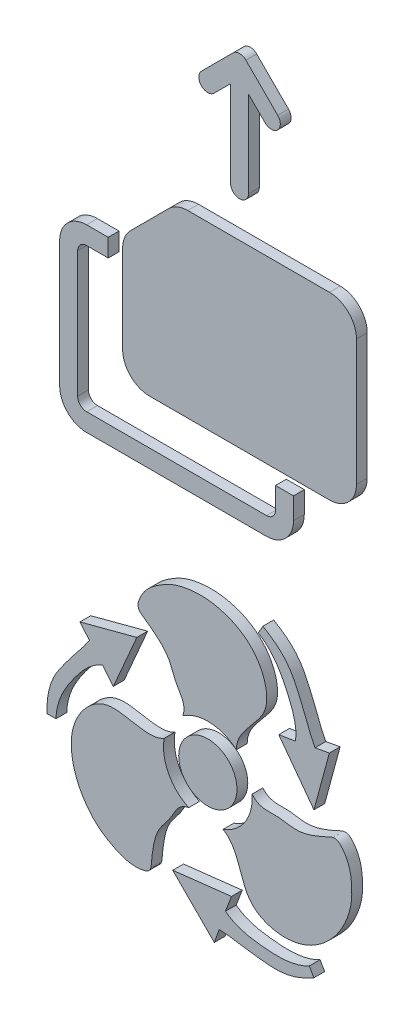
SolidWorks part; units mm, degrees
ref_plane "Plan de face" through (0, 0, 0) normal (0, 0, 1) x (1, 0, 0)
ref_plane "Plan de dessus" through (0, 0, 0) normal (0, 1, 0) x (1, 0, 0)
ref_plane "Plan de droite" through (0, 0, 0) normal (1, 0, 0) x (0, 0, -1)
sketch "Esquisse1" plane through (0, 0, 0) normal (0, 0, 1) x (1, 0, 0)
  line L0 (80.7187, -5.6862) -> (79.9221, -5.8311) construction
  line L1 (77.0254, -1.426) -> (76.7701, -1.8683) construction
  line L2 (78.8351, -6.0582) -> (77.9051, -6.2071) construction
  line L3 (77.9051, -6.2071) -> (79.8625, -8.8495) construction
  line L4 (79.8625, -8.8495) -> (80.7187, -5.6862) construction
  line L5 (66.8516, -6.3076) -> (67.3754, -6.925)
  line L6 (65.0089, -11.6362) -> (65.5195, -11.6362)
  line L7 (68.1156, -7.7529) -> (68.7095, -8.4839)
  line L8 (68.7095, -8.4839) -> (70.0193, -5.4674)
  line L9 (70.0193, -5.4674) -> (66.8516, -6.3076)
  line L10 (66.8516, -6.3076) -> (67.3754, -6.925)
  line L11 (65.0089, -11.6362) -> (65.5195, -11.6362)
  line L12 (68.1156, -7.7529) -> (68.7095, -8.4839)
  line L13 (68.7095, -8.4839) -> (70.0193, -5.4674)
  line L14 (70.0193, -5.4674) -> (66.8516, -6.3076)
  line L15 (74.3234, -18.0062) -> (74.5961, -17.2438)
  line L16 (79.8594, -16.9377) -> (79.6041, -16.4955)
  line L17 (74.943, -16.1889) -> (75.279, -15.309)
  line L18 (75.279, -15.309) -> (72.0119, -15.683)
  line L19 (72.0119, -15.683) -> (74.3234, -18.0062)
  line L20 (74.3234, -18.0062) -> (74.5961, -17.2438)
  line L21 (79.8594, -16.9377) -> (79.6041, -16.4955)
  line L22 (74.943, -16.1889) -> (75.279, -15.309)
  line L23 (75.279, -15.309) -> (72.0119, -15.683)
  line L24 (72.0119, -15.683) -> (74.3234, -18.0062)
  line L25 (80.7187, -5.6862) -> (79.9221, -5.8311)
  line L26 (77.0254, -1.426) -> (76.7701, -1.8683)
  line L27 (78.8351, -6.0582) -> (77.9051, -6.2071)
  line L28 (77.9051, -6.2071) -> (79.8625, -8.8495)
  line L29 (79.8625, -8.8495) -> (80.7187, -5.6862)
  line L30 (74.3112, 22.8787) -> (75.2254, 23.7929) construction
  line L31 (75.2254, 23.7929) -> (75.2254, 19) construction
  line L32 (76.2254, 19) -> (76.2254, 23.7929) construction
  line L33 (76.2254, 23.7929) -> (77.1396, 22.8787) construction
  line L34 (77.8467, 23.5858) -> (76.079, 25.3536) construction
  line L35 (75.3718, 25.3536) -> (73.6041, 23.5858) construction
  line L36 (70.7254, 6.5) -> (80.7254, 6.5) construction
  line L37 (82.2254, 8) -> (82.2254, 15) construction
  line L38 (80.7254, 16.5) -> (72.8467, 16.5) construction
  line L39 (71.7861, 16.0607) -> (69.6647, 13.9393) construction
  line L40 (69.2254, 12.8787) -> (69.2254, 8) construction
  line L41 (66.7254, 4.5) -> (66.7254, 11.5) construction
  line L42 (67.2254, 12) -> (68.4254, 12) construction
  line L43 (68.4254, 12) -> (68.4254, 13) construction
  line L44 (68.4254, 13) -> (67.2254, 13) construction
  line L45 (65.7254, 11.5) -> (65.7254, 4.5) construction
  line L46 (67.2254, 3) -> (77.2254, 3) construction
  line L47 (78.7254, 4.5) -> (78.7254, 5.7) construction
  line L48 (78.7254, 5.7) -> (77.7254, 5.7) construction
  line L49 (77.7254, 5.7) -> (77.7254, 4.5) construction
  line L50 (77.2254, 4) -> (67.2254, 4) construction
  line L51 (74.3112, 22.8787) -> (75.2254, 23.7929)
  line L52 (75.2254, 23.7929) -> (75.2254, 19)
  line L53 (76.2254, 19) -> (76.2254, 23.7929)
  line L54 (76.2254, 23.7929) -> (77.1396, 22.8787)
  line L55 (77.8467, 23.5858) -> (76.079, 25.3536)
  line L56 (75.3718, 25.3536) -> (73.6041, 23.5858)
  line L57 (70.7254, 6.5) -> (80.7254, 6.5)
  line L58 (82.2254, 8) -> (82.2254, 15)
  line L59 (80.7254, 16.5) -> (72.8467, 16.5)
  line L60 (71.7861, 16.0607) -> (69.6647, 13.9393)
  line L61 (69.2254, 12.8787) -> (69.2254, 8)
  line L62 (66.7254, 4.5) -> (66.7254, 11.5)
  line L63 (67.2254, 12) -> (68.4254, 12)
  line L64 (68.4254, 12) -> (68.4254, 13)
  line L65 (68.4254, 13) -> (67.2254, 13)
  line L66 (65.7254, 11.5) -> (65.7254, 4.5)
  line L67 (67.2254, 3) -> (77.2254, 3)
  line L68 (78.7254, 4.5) -> (78.7254, 5.7)
  line L69 (78.7254, 5.7) -> (77.7254, 5.7)
  line L70 (77.7254, 5.7) -> (77.7254, 4.5)
  line L71 (77.2254, 4) -> (67.2254, 4)
  arc A0 (74.806, -12.3188) -> (76.4239, -9.8094) centre (73.9646, -10) ccw construction
  arc A1 (71.5358, -9.5693) -> (72.9, -12.2251) centre (73.9646, -10) ccw
  arc A2 (71.5358, -9.5693) -> (72.9, -12.2251) centre (73.9646, -10) ccw
  arc A3 (75.552, -8.1119) -> (72.5698, -7.9655) centre (73.9646, -10) ccw
  arc A4 (75.552, -8.1119) -> (72.5698, -7.9655) centre (73.9646, -10) ccw
  circle A5 centre (73.9646, -10) radius 1.62 construction
  arc A6 (74.806, -12.3188) -> (76.4239, -9.8094) centre (73.9646, -10) ccw
  circle A7 centre (73.9646, -10) radius 1.62
  arc A8 (75.2254, 19) -> (76.2254, 19) centre (75.7254, 19) ccw construction
  arc A9 (77.1396, 22.8787) -> (77.8467, 23.5858) centre (77.4932, 23.2322) ccw construction
  arc A10 (76.079, 25.3536) -> (75.3718, 25.3536) centre (75.7254, 25) ccw construction
  arc A11 (73.6041, 23.5858) -> (74.3112, 22.8787) centre (73.9576, 23.2322) ccw construction
  arc A12 (69.2254, 8) -> (70.7254, 6.5) centre (70.7254, 8) ccw construction
  arc A13 (80.7254, 6.5) -> (82.2254, 8) centre (80.7254, 8) ccw construction
  arc A14 (82.2254, 15) -> (80.7254, 16.5) centre (80.7254, 15) ccw construction
  arc A15 (72.8467, 16.5) -> (71.7861, 16.0607) centre (72.8467, 15) ccw construction
  arc A16 (69.6647, 13.9393) -> (69.2254, 12.8787) centre (70.7254, 12.8787) ccw construction
  arc A17 (66.7254, 4.5) -> (67.2254, 4) centre (67.2254, 4.5) ccw construction
  arc A18 (67.2254, 12) -> (66.7254, 11.5) centre (67.2254, 11.5) ccw construction
  arc A19 (67.2254, 13) -> (65.7254, 11.5) centre (67.2254, 11.5) ccw construction
  arc A20 (65.7254, 4.5) -> (67.2254, 3) centre (67.2254, 4.5) ccw construction
  arc A21 (77.2254, 3) -> (78.7254, 4.5) centre (77.2254, 4.5) ccw construction
  arc A22 (77.2254, 4) -> (77.7254, 4.5) centre (77.2254, 4.5) ccw construction
  arc A23 (75.2254, 19) -> (76.2254, 19) centre (75.7254, 19) ccw
  arc A24 (77.1396, 22.8787) -> (77.8467, 23.5858) centre (77.4932, 23.2322) ccw
  arc A25 (76.079, 25.3536) -> (75.3718, 25.3536) centre (75.7254, 25) ccw
  arc A26 (73.6041, 23.5858) -> (74.3112, 22.8787) centre (73.9576, 23.2322) ccw
  arc A27 (69.2254, 8) -> (70.7254, 6.5) centre (70.7254, 8) ccw
  arc A28 (80.7254, 6.5) -> (82.2254, 8) centre (80.7254, 8) ccw
  arc A29 (82.2254, 15) -> (80.7254, 16.5) centre (80.7254, 15) ccw
  arc A30 (72.8467, 16.5) -> (71.7861, 16.0607) centre (72.8467, 15) ccw
  arc A31 (69.6647, 13.9393) -> (69.2254, 12.8787) centre (70.7254, 12.8787) ccw
  arc A32 (66.7254, 4.5) -> (67.2254, 4) centre (67.2254, 4.5) ccw
  arc A33 (67.2254, 12) -> (66.7254, 11.5) centre (67.2254, 11.5) ccw
  arc A34 (67.2254, 13) -> (65.7254, 11.5) centre (67.2254, 11.5) ccw
  arc A35 (65.7254, 4.5) -> (67.2254, 3) centre (67.2254, 4.5) ccw
  arc A36 (77.2254, 3) -> (78.7254, 4.5) centre (77.2254, 4.5) ccw
  arc A37 (77.2254, 4) -> (77.7254, 4.5) centre (77.2254, 4.5) ccw
  spline S0 degree 3 poles (2853.4427, 1137.0231) (58.2851, -46.9918) (85.55, -18.1264) (78.9456, -3.542) (78.5929, -2.7745) (68.2775, 9.4106) (-5.6043, -55.9986) (2180.7071, 2137.1548) knots -8.287182 -8.287182 -8.287182 -8.287182 0.322858 0.451826 0.608228 0.790301 9.167729 9.167729 9.167729 9.167729 only from (79.9221, -5.8311) to (77.0254, -1.426) construction
  spline S1 degree 3 poles (-801.0947, 3893.711) (128.4307, -164.1084) (79.8155, -2.705) (67.3522, -10.0238) (66.6988, -10.8556) (66.3508, -11.9084) (66.3679, -12.9817) (66.672, -14.1036) (67.2485, -15.0455) (67.9262, -15.7476) (68.5915, -16.146) (69.2035, -16.4406) (69.8087, -16.5606) (70.288, -16.5387) (70.6603, -16.43) (70.8254, -16.1572) (70.8202, -15.7988) (70.9018, -15.2996) (70.9946, -14.6485) (71.283, -13.9494) (78.0625, -7.0579) (34.8309, 37.4368) (3123.351, -2599.2438) knots -1.960638 -1.960638 -1.960638 -1.960638 0.177515 0.224652 0.289489 0.345336 0.400887 0.461026 0.531696 0.577426 0.617679 0.656656 0.687064 0.71613 0.735073 0.745884 0.765115 0.791853 0.828117 0.871557 0.91134 2.379171 2.379171 2.379171 2.379171 only from (71.5358, -9.5693) to (72.9, -12.2251)
  spline S2 degree 3 poles (71.5358, -9.5693) (70.5858, -10.1323) (68.9557, -9.0822) (67.3522, -10.0238) (66.6988, -10.8556) (66.3508, -11.9084) (66.3679, -12.9817) (66.672, -14.1036) (67.2485, -15.0455) (67.9262, -15.7476) (68.5915, -16.146) (69.2035, -16.4406) (69.8087, -16.5606) (70.288, -16.5387) (70.6603, -16.43) (70.8254, -16.1572) (70.8202, -15.7988) (70.9018, -15.2996) (70.9946, -14.6485) (71.283, -13.9494) (72.0343, -13.1857) (72.234, -12.3407) (72.9, -12.2251) knots 0 0 0 0 0.177515 0.224652 0.289489 0.345336 0.400887 0.461026 0.531696 0.577426 0.617679 0.656656 0.687064 0.71613 0.735073 0.745884 0.765115 0.791853 0.828117 0.871557 0.91134 1 1 1 1
  spline S3 degree 3 poles (3892.2071, -1204.032) (-86.7303, 19.8851) (77.3568, -18.7145) (77.2502, -4.2616) (76.8564, -3.2799) (76.1187, -2.4521) (75.1807, -1.9302) (74.057, -1.6326) (72.953, -1.6609) (72.0062, -1.8968) (71.3285, -2.2738) (70.7673, -2.6565) (70.3608, -3.1206) (70.1402, -3.5466) (70.0482, -3.9234) (70.2018, -4.2028) (70.5148, -4.3775) (70.9064, -4.6978) (71.4238, -5.1037) (71.8851, -5.703) (74.4635, -15.02) (134.6129, 0.1723) (-3693.0796, -1356.2242) knots -1.960638 -1.960638 -1.960638 -1.960638 0.177515 0.224652 0.289489 0.345336 0.400887 0.461026 0.531696 0.577426 0.617679 0.656656 0.687064 0.71613 0.735073 0.745884 0.765115 0.791853 0.828117 0.871557 0.91134 2.379171 2.379171 2.379171 2.379171 only from (75.552, -8.1119) to (72.5698, -7.9655)
  spline S4 degree 3 poles (-3107.5593, 2425.5803) (121.6939, -7.0927) (76.1075, 5.3491) (65.8812, -8.9153) (65.3929, -9.6044) (59.4924, -26.0385) (172.3458, -62.0292) (-3805.053, 998.3532) knots -9.143521 -9.143521 -9.143521 -9.143521 0.322858 0.451826 0.608228 0.790301 9.984493 9.984493 9.984493 9.984493 only from (67.3754, -6.925) to (65.0089, -11.6362)
  spline S5 degree 3 poles (3988.4954, 759.8664) (140.9785, -102.058) (55.2995, -25.6736) (75.5806, 4.1489) (109.32, 5.8187) (2427.4353, -3237.1323) knots -11.594051 -11.594051 -11.594051 -11.594051 0.353975 0.561821 10.719218 10.719218 10.719218 10.719218 only from (65.5195, -11.6362) to (68.1156, -7.7529)
  spline S6 degree 3 poles (67.3754, -6.925) (67.0716, -7.4234) (66.5191, -8.0256) (65.8812, -8.9153) (65.3929, -9.6044) (65.0536, -10.5495) (65.0183, -11.2595) (65.0089, -11.6362) knots 0 0 0 0 0.322858 0.451826 0.608228 0.790301 1 1 1 1
  spline S7 degree 3 poles (65.5195, -11.6362) (65.5336, -11.0571) (65.8377, -10.1777) (66.7466, -8.8412) (67.4282, -8.0251) (68.1156, -7.7529) knots 0 0 0 0 0.353975 0.561821 1 1 1 1
  spline S8 degree 3 poles (75.552, -8.1119) (75.5393, -7.0078) (77.2639, -6.1211) (77.2502, -4.2616) (76.8564, -3.2799) (76.1187, -2.4521) (75.1807, -1.9302) (74.057, -1.6326) (72.953, -1.6609) (72.0062, -1.8968) (71.3285, -2.2738) (70.7673, -2.6565) (70.3608, -3.1206) (70.1402, -3.5466) (70.0482, -3.9234) (70.2018, -4.2028) (70.5148, -4.3775) (70.9064, -4.6978) (71.4238, -5.1037) (71.8851, -5.703) (72.1708, -6.7355) (72.8028, -7.331) (72.5698, -7.9655) knots 0 0 0 0 0.177515 0.224652 0.289489 0.345336 0.400887 0.461026 0.531696 0.577426 0.617679 0.656656 0.687064 0.71613 0.735073 0.745884 0.765115 0.791853 0.828117 0.871557 0.91134 1 1 1 1
  spline S9 degree 3 poles (-915.886, -2831.3939) (-20.2333, -15.8889) (70.5023, 12.3886) (84.7547, -17.1179) (72.5757, -43.2456) (-2902.4148, -337.0899) knots -10.486085 -10.486085 -10.486085 -10.486085 0.353975 0.561821 9.787433 9.787433 9.787433 9.787433 only from (76.7701, -1.8683) to (78.8351, -6.0582) construction
  spline S10 degree 3 poles (-444.548, -3983.0706) (47.5821, 29.8812) (59.6004, -15.8187) (77.0668, -17.5427) (77.9078, -17.621) (95.0903, -14.514) (69.8325, 101.2152) (1140.2138, -3873.5044) knots -9.143521 -9.143521 -9.143521 -9.143521 0.322858 0.451826 0.608228 0.790301 9.984493 9.984493 9.984493 9.984493 only from (74.5961, -17.2438) to (79.8594, -16.9377)
  spline S11 degree 3 poles (-2550.0248, 2995.1499) (120.1822, 94.0648) (96.8708, -18.3276) (60.9032, -15.6749) (42.5875, 12.7094) (1692.0077, 3641.7316) knots -11.594051 -11.594051 -11.594051 -11.594051 0.353975 0.561821 10.719218 10.719218 10.719218 10.719218 only from (79.6041, -16.4955) to (74.943, -16.1889)
  spline S12 degree 3 poles (74.5961, -17.2438) (75.1796, -17.2578) (75.9774, -17.4352) (77.0668, -17.5427) (77.9078, -17.621) (78.8959, -17.4424) (79.5285, -17.118) (79.8594, -16.9377) knots 0 0 0 0 0.322858 0.451826 0.608228 0.790301 1 1 1 1
  spline S13 degree 3 poles (79.6041, -16.4955) (79.0955, -16.7729) (78.1819, -16.9492) (76.57, -16.8304) (75.5224, -16.6481) (74.943, -16.1889) knots 0 0 0 0 0.353975 0.561821 1 1 1 1
  spline S14 degree 3 poles (-2136.6135, -2039.1913) (161.2879, 93.9704) (65.7707, -9.1759) (77.2913, -15.7146) (78.3384, -15.8645) (79.4242, -15.6395) (80.3451, -15.0881) (81.1647, -14.2638) (81.6922, -13.2935) (81.9613, -12.3556) (81.9737, -11.5802) (81.9228, -10.9029) (81.7242, -10.3188) (81.4655, -9.9147) (81.1853, -9.6466) (80.8665, -9.64) (80.5587, -9.8237) (80.0855, -10.0026) (79.4752, -10.2478) (78.7256, -10.3477) (70.1652, -8.1288) (55.3563, -57.6199) (609.7558, 2942.2664) knots -1.772822 -1.772822 -1.772822 -1.772822 0.177515 0.224652 0.289489 0.345336 0.400887 0.461026 0.531696 0.577426 0.617679 0.656656 0.687064 0.71613 0.735073 0.745884 0.765115 0.791853 0.828117 0.871557 0.91134 2.246989 2.246989 2.246989 2.246989 only from (74.806, -12.3188) to (76.4239, -9.8094) construction
  spline S15 degree 3 poles (79.9221, -5.8311) (79.6424, -5.3189) (79.3972, -4.5392) (78.9456, -3.542) (78.5929, -2.7745) (77.9442, -2.0082) (77.3469, -1.6225) (77.0254, -1.426) knots 0 0 0 0 0.322858 0.451826 0.608228 0.790301 1 1 1 1
  spline S16 degree 3 poles (76.7701, -1.8683) (77.2646, -2.1701) (77.8741, -2.873) (78.5771, -4.3285) (78.943, -5.3268) (78.8351, -6.0582) knots 0 0 0 0 0.353975 0.561821 1 1 1 1
  spline S17 degree 3 poles (74.806, -12.3188) (75.7685, -12.8599) (75.6741, -14.7968) (77.2913, -15.7146) (78.3384, -15.8645) (79.4242, -15.6395) (80.3451, -15.0881) (81.1647, -14.2638) (81.6922, -13.2935) (81.9613, -12.3556) (81.9737, -11.5802) (81.9228, -10.9029) (81.7242, -10.3188) (81.4655, -9.9147) (81.1853, -9.6466) (80.8665, -9.64) (80.5587, -9.8237) (80.0855, -10.0026) (79.4752, -10.2478) (78.7256, -10.3477) (77.6886, -10.0789) (76.8569, -10.3283) (76.4239, -9.8094) knots 0 0 0 0 0.177515 0.224652 0.289489 0.345336 0.400887 0.461026 0.531696 0.577426 0.617679 0.656656 0.687064 0.71613 0.735073 0.745884 0.765115 0.791853 0.828117 0.871557 0.91134 1 1 1 1
  dimension "D1" = 0
  dimension "D2" = 0
  dimension "D3" = 0
  dimension "D4" = 0
extrude "Boss.-Extru.1" add sketch "Esquisse1" along normal up to surface (0.6 mm away)
